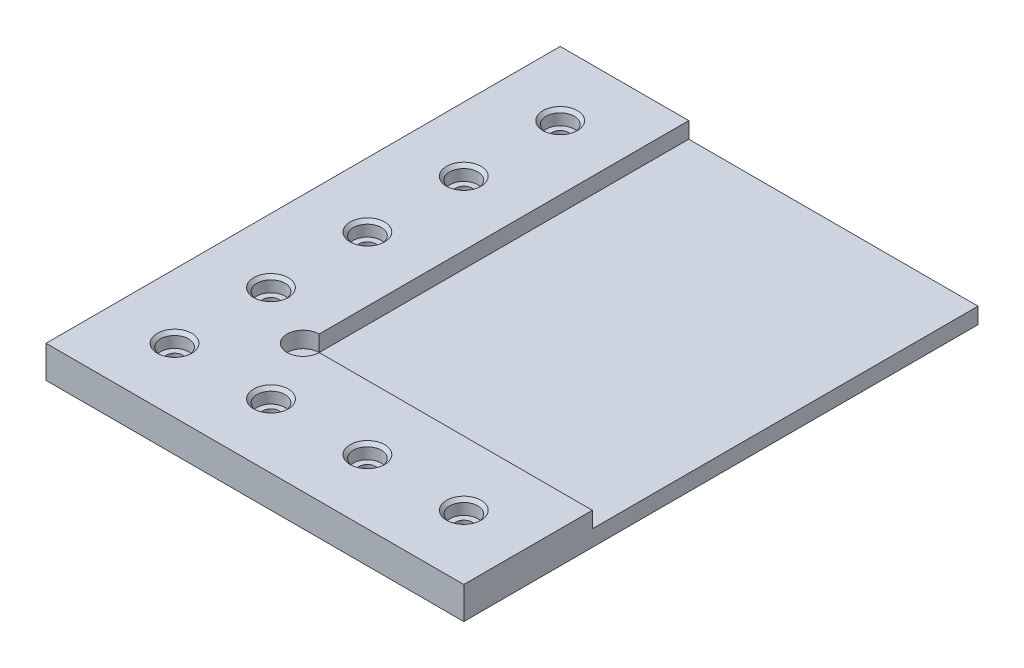
SolidWorks part; units mm, degrees
ref_plane "Front Plane" through (0, 0, 0) normal (0, 0, 1) x (1, 0, 0)
ref_plane "Top Plane" through (0, 0, 0) normal (0, 1, 0) x (1, 0, 0)
ref_plane "Right Plane" through (0, 0, 0) normal (1, 0, 0) x (0, 0, -1)
sketch "Base Plate" plane through (0, 0, 0) normal (0, 1, 0) x (1, 0, 0)
  line L1 (-41.275, 50.8) -> (41.275, 50.8)
  line L2 (-41.275, 50.8) -> (-41.275, -50.8)
  line L3 (-41.275, -50.8) -> (41.275, -50.8)
  line L4 (41.275, 50.8) -> (41.275, -50.8)
  line L5 (-41.275, 50.8) -> (41.275, -50.8) construction
  line L6 (-41.275, -50.8) -> (41.275, 50.8) construction
  point P0 (0, 0)
  dimension "D1" = 82.55
  dimension "D2" = 80
  dimension "D3" = 101.6
  dimension "D4" = 80
extrude "Main Body" add sketch "Base Plate" along normal blind 6.35
sketch "Hole Positions" plane through (0, 6.35, 0) normal (0, 1, 0) x (1, 0, 0)
  point P0 (-28.575, -38.1)
  point P2 (-9.525, -38.1)
  point P4 (9.525, -38.1)
  point P6 (28.575, -38.1)
  point P8 (-28.575, -19.05)
  point P10 (-28.575, 0)
  point P12 (-28.575, 19.05)
  point P14 (-28.575, 38.1)
  dimension "D1" = 0
  dimension "D2" = 19.05
  dimension "D3" = 19.05
  dimension "D4" = 0
  dimension "D5" = 0
  dimension "D6" = 19.05
  dimension "D7" = 19.05
  dimension "D8" = 0
  dimension "D9" = 19.05
  dimension "D10" = 0
hole_wizard "Mounting Holes (CBORE) " positions "Hole Positions" profile "Hole Profile" counterbore size "#4" standard "ANSI Inch" end condition through all
sketch "Hole Profile" plane through (-28.575, 6.35, 38.1) normal (1, 0, 0) x (0, 0, 1)
  line L0 (0, 0) -> (0, 6.35)
  line L1 (0, 6.35) -> (1.6319, 6.35)
  line L3 (1.6319, 6.35) -> (1.632, 2.8448)
  line L4 (2.7788, 2.8448) -> (1.632, 2.8448)
  line L5 (2.7788, 2.8448) -> (2.7788, 0.635)
  line L6 (2.7788, 0.635) -> (3.4138, 0)
  line L7 (3.4138, 0) -> (0, 0)
  line L8 (-2.7788, 0.635) -> (-3.4138, 0) construction
  line L11 (0, -6.35) -> (0, 107.95) construction
  dimension "Thru Hole Dia." = 3.2639
  dimension "Thru Hole Depth" = 6.35
  dimension "C'Bore Dia." = 5.5575
  dimension "C'Bore Depth" = 2.8448
  dimension "Near C'Sink Dia." = 6.8275
  dimension "Near C'Sink Angle" = 90
sketch "L-Area Exclusion  " plane through (0, 6.35, 0) normal (0, 1, 0) x (1, 0, 0)
  line L0 (41.275, 50.8) -> (-41.275, 50.8) construction
  line L1 (41.275, 50.8) -> (-15.875, 50.8)
  line L2 (41.275, 50.8) -> (41.275, -25.4)
  line L3 (41.275, -25.4) -> (-15.875, -25.4)
  line L4 (-15.875, 50.8) -> (-15.875, -25.4)
  line L5 (-41.275, 50.8) -> (-41.275, -50.8) construction
  line L6 (41.275, -50.8) -> (41.275, 50.8) construction
  line L7 (-41.275, -50.8) -> (41.275, -50.8) construction
  dimension "D1" = 0
  dimension "D2" = 25.4
  dimension "D3" = 0
  dimension "D4" = 25.4
extrude "L-Area Step Cut " cut sketch "L-Area Exclusion  " against normal blind 3.175
sketch "Relief Circle Sketch" plane through (0, 6.35, 0) normal (0, 1, 0) x (1, 0, 0)
  circle A0 centre (-15.875, -25.4) radius 3.175
  point P2 (-106.4893, -25.1894)
  dimension "D1" = 4.9477
extrude "Substrate Relief Pocket" cut sketch "Relief Circle Sketch" against normal blind 3.175
